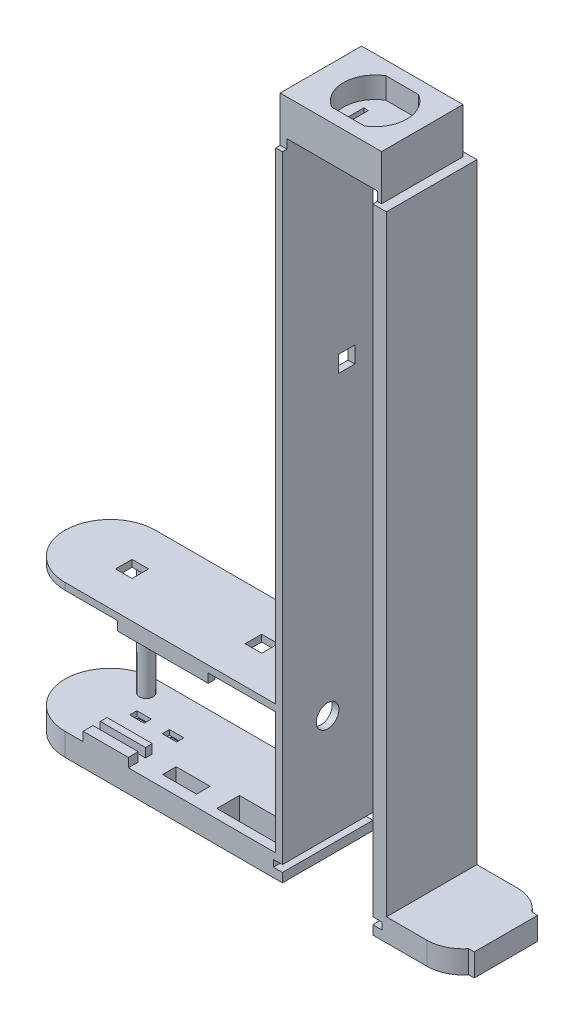
SolidWorks part; units mm, degrees
material "PVC Rigid"
ref_plane "Front Plane" through (0, 0, 0) normal (0, 0, 1) x (1, 0, 0)
ref_plane "Top Plane" through (0, 0, 0) normal (0, 1, 0) x (1, 0, 0)
ref_plane "Right Plane" through (0, 0, 0) normal (1, 0, 0) x (0, 0, -1)
sketch "Sketch2" plane through (0, 0, 0) normal (0, 1, 0) x (1, 0, 0)
  line L0 (-97.0727, 0) -> (97.0727, 0) construction
  line L1 (0, 44.8562) -> (0, -44.8562) construction
  line L2 (0, 10) -> (80, 10)
  line L3 (0, -10) -> (80, -10)
  line L5 (86.245, 7) -> (87.485, 7)
  line L6 (87.485, 7) -> (87.485, -7)
  line L7 (87.485, -7) -> (86.245, -7)
  arc A0 (0, 10) -> (0, -10) centre (0, 0) ccw
  arc A1 (80, 10) -> (86.245, 7) centre (80, 2) cw
  arc A2 (80, -10) -> (86.245, -7) centre (80, -2) ccw
  dimension "D1" = 10
  dimension "D4" = 8
  dimension "D5" = 8
  dimension "D2" = 80
  dimension "D3" = 80
  dimension "D6" = 7
  dimension "D7" = 7
  dimension "D8" = 1.24
  dimension "D9" = 1.24
extrude "Boss-Extrude1" add sketch "Sketch2" along normal blind 5
sketch "Sketch3" plane through (0, 5, 0) normal (0, 1, 0) x (1, 0, 0)
  line L0 (48.0657, 27.5037) -> (48.0657, -29.4655) construction
  line L2 (80, 10) -> (0, 10) construction
  line L3 (48.0657, 10) -> (46.5657, 10)
  line L4 (48.0657, 10) -> (48.0657, -10)
  line L5 (48.0657, -10) -> (46.5657, -10)
  line L6 (46.5657, 10) -> (46.5657, -10)
  line L7 (0, -10) -> (80, -10) construction
  line L8 (80, 10) -> (0, 10) construction
  line L9 (68.0657, 10) -> (71.0657, 10)
  line L10 (68.0657, 10) -> (68.0657, -10)
  line L11 (68.0657, -10) -> (71.0657, -10)
  line L12 (71.0657, 10) -> (71.0657, -10)
  line L13 (0, -10) -> (80, -10) construction
  dimension "D1" = 1.5
  dimension "D2" = 3
  dimension "D3" = 20
extrude "Boss-Extrude2" add sketch "Sketch3" along normal blind 145
ref_plane "Plane1" through (0, 32, 0) normal (0, 1, 0) x (1, 0, 0)
sketch "Sketch4" plane through (0, 32, 0) normal (0, 1, 0) x (1, 0, 0)
  line L0 (0, 10) -> (46.5657, 10)
  line L1 (46.5657, 10) -> (46.5657, -10) construction
  line L2 (46.5657, 10) -> (46.5657, -10) construction
  line L3 (0, -10) -> (46.5657, -10)
  line L4 (46.5657, -10) -> (46.5657, 10)
  arc A0 (0, 10) -> (0, -10) centre (0, 0) ccw
  arc A1 (0, 10) -> (0, -10) centre (0, 0) ccw construction
extrude "Boss-Extrude3" add sketch "Sketch4" along normal blind 1.5
sketch "Sketch5" plane through (0, 150, 0) normal (0, 1, 0) x (1, 0, 0)
  line L1 (68.0657, 10) -> (48.0657, 10)
  line L2 (68.0657, 10) -> (68.0657, -10)
  line L3 (68.0657, -10) -> (48.0657, -10)
  line L4 (48.0657, 10) -> (48.0657, -10)
extrude "Boss-Extrude4" add sketch "Sketch5" against normal blind 8
sketch "Sketch7" plane through (0, 0, 10) normal (0, 0, 1) x (1, 0, 0)
  line L0 (48.0657, 16.8561) -> (48.0657, -1.4698) construction
  line L1 (48.0657, 142) -> (48.0657, 5) construction
  line L2 (68.0657, 16.8561) -> (68.0657, -2.6062) construction
  line L3 (68.0657, 142) -> (68.0657, 5) construction
  line L4 (48.0657, 5) -> (48.0657, 3.5)
  line L5 (48.0657, 3.5) -> (46.0657, 3.5)
  line L6 (46.0657, 3.5) -> (46.0657, 2)
  line L7 (46.0657, 2) -> (48.0657, 2)
  line L8 (48.0657, 2) -> (48.0657, 0)
  line L9 (48.0657, 0) -> (68.0657, 0)
  line L10 (0, 0) -> (80, 0) construction
  line L11 (68.0657, 0) -> (68.0657, 2)
  line L12 (68.0657, 2) -> (70.0657, 2)
  line L13 (70.0657, 2) -> (70.0657, 3.5)
  line L14 (70.0657, 3.5) -> (68.0657, 3.5)
  line L15 (68.0657, 3.5) -> (68.0657, 5)
  line L16 (68.0657, 5) -> (48.0657, 5)
  line L17 (0, 5) -> (46.5657, 5) construction
  line L18 (0, 5) -> (0, 0) construction
  dimension "D1" = 1.5
  dimension "D2" = 1.5
  dimension "D3" = 1.5
  dimension "D4" = 1.5
  dimension "D5" = 2
  dimension "D6" = 2
  dimension "D7" = 48.0657
extrude "Cut-Extrude1" cut sketch "Sketch7" against normal blind 20
sketch "Sketch8" plane through (0, 5, 0) normal (0, 1, 0) x (1, 0, 0)
  circle A0 centre (1.6533, 6.3042) radius 1.5
  dimension "D1" = 1.5
extrude "Boss-Extrude5" add sketch "Sketch8" along normal up to next
sketch "Sketch9" plane through (46.5657, 0, 0) normal (-1, 0, 0) x (0, 0, 1)
  line L0 (10, 32) -> (-10, 32) construction
  line L1 (10, 32) -> (10, 5) construction
  circle A0 centre (0, 27) radius 2.5
  dimension "D1" = 5
  dimension "D2" = 5
  dimension "D3" = 10
extrude "Cut-Extrude2" cut sketch "Sketch9" against normal blind 1.5 contours A0
sketch "Sketch10" plane through (0, 0, 0) normal (0, 1, 0) x (1, 0, 0)
  line L0 (71.0657, 21.0712) -> (71.0657, -27.514) construction
  line L1 (71.0657, -10) -> (71.0657, 10) construction
  line L2 (71.0657, 10) -> (91.8634, 10) construction
  line L3 (71.0657, -10) -> (94.8231, -10) construction
  line L4 (80, -10) -> (80, 10) construction
  dimension "D1" = 8.9343
  dimension "D2" = 20
sketch "Sketch11" plane through (0, 33.5, 0) normal (0, 1, 0) x (1, 0, 0)
  line L0 (0, 0) -> (40.7107, 0) construction
  line L1 (3, 1.825) -> (6.65, 1.825)
  line L2 (3, 1.825) -> (3, -1.825)
  line L3 (3, -1.825) -> (6.65, -1.825)
  line L4 (6.65, 1.825) -> (6.65, -1.825)
  line L6 (31.65, 1.825) -> (35.3, 1.825)
  line L7 (31.65, 1.825) -> (31.65, -1.825)
  line L8 (31.65, -1.825) -> (35.3, -1.825)
  line L9 (35.3, 1.825) -> (35.3, -1.825)
  point P11 (35.3, 0)
  dimension "D1" = 3.65
  dimension "D2" = 3.65
  dimension "D3" = 3
  dimension "D4" = 1.825
  dimension "D5" = 3.65
  dimension "D6" = 3.65
  dimension "D7" = 3.65
  dimension "D8" = 25
extrude "Cut-Extrude3" cut sketch "Sketch11" against normal up to next
sketch "Sketch12" plane through (46.5657, 0, 0) normal (-1, 0, 0) x (0, 0, 1)
  line L0 (-10, 150) -> (-10, 33.5) construction
  line L1 (-6, 95) -> (-2.35, 95)
  line L2 (-6, 95) -> (-6, 91.35)
  line L3 (-6, 91.35) -> (-2.35, 91.35)
  line L4 (-2.35, 95) -> (-2.35, 91.35)
  line L5 (-10, 150) -> (10, 150) construction
  dimension "D1" = 3.65
  dimension "D2" = 4
  dimension "D3" = 55
extrude "Cut-Extrude4" cut sketch "Sketch12" against normal up to next
sketch "Sketch13" plane through (0, 0, 0) normal (0, 0, 1) x (1, 0, 0)
  line L0 (48.0657, 0) -> (48.0657, 150) construction
  line L1 (46.5657, 150) -> (71.0657, 150) construction
  dimension "D1" = 150
sketch "Sketch14" plane through (0, 150, 0) normal (0, 1, 0) x (1, 0, 0)
  line L0 (54.9613, 6) -> (62.1713, 6)
  line L1 (54.9613, -6) -> (62.1713, -6)
  line L3 (46.5657, -10) -> (71.0657, -10) construction
  line L4 (46.5657, 10) -> (46.5657, -10) construction
  arc A0 (54.9613, 6) -> (54.9613, -6) centre (58.5657, 0) ccw
  arc A1 (62.1713, 6) -> (62.1713, -6) centre (58.5669, 0) cw
  dimension "D2" = 14
  dimension "D1" = 12
  dimension "D3" = 7.21
  dimension "D4" = 10
  dimension "D5" = 12
extrude "Cut-Extrude5" cut sketch "Sketch14" against normal blind 4.7
sketch "Sketch15" plane through (0, 145.3, 0) normal (0, 1, 0) x (1, 0, 0)
  line L0 (53.9613, 2.1) -> (53.9613, -2.1)
  line L1 (53.9613, 2.1) -> (54.9613, 2.1)
  line L2 (54.9613, 2.1) -> (54.9613, -2.1)
  line L3 (54.9613, -2.1) -> (53.9613, -2.1)
  line L5 (62.1713, 6) -> (54.9613, 6) construction
  line L6 (58.5663, 7.0131) -> (58.5663, -6.3145) construction
  line L8 (62.1713, 2.1) -> (62.1713, -2.1)
  line L9 (63.1713, 2.1) -> (62.1713, 2.1)
  line L10 (63.1713, 2.1) -> (63.1713, -2.1)
  line L11 (62.1713, -2.1) -> (63.1713, -2.1)
  dimension "D1" = 4.2
  dimension "D2" = 1
  dimension "D3" = 3.9
  dimension "D4" = 0
  dimension "D5" = 3.605
extrude "Cut-Extrude7" cut sketch "Sketch15" against normal up to next
sketch "Sketch17" plane through (0, 32, 0) normal (0, -1, 0) x (1, 0, 0)
  line L1 (11.65, 10) -> (31.65, 10)
  line L2 (11.65, 10) -> (11.65, 8.5)
  line L3 (11.65, 8.5) -> (31.65, 8.5)
  line L4 (31.65, 10) -> (31.65, 8.5)
  line L5 (11.65, 10) -> (31.65, 8.5) construction
  line L6 (11.65, 8.5) -> (31.65, 10) construction
  line L7 (0, 10) -> (46.5657, 10) construction
  line L8 (31.65, 1.825) -> (31.65, -1.825) construction
  line L10 (11.65, 6.9) -> (31.65, 6.9)
  line L11 (11.65, 6.9) -> (11.65, 5.4)
  line L12 (11.65, 5.4) -> (31.65, 5.4)
  line L13 (31.65, 6.9) -> (31.65, 5.4)
  point P0 (21.65, 9.25)
  dimension "D1" = 1.5
  dimension "D2" = 20
  dimension "D3" = 1.5
  dimension "D4" = 20
  dimension "D5" = 1.6
extrude "Boss-Extrude6" add sketch "Sketch17" along normal blind 2
sketch "Sketch19" plane through (0, 0, 0) normal (0, -1, 0) x (1, 0, 0)
  line L0 (48.0657, -10) -> (48.0657, 10) construction
  line L1 (31.5657, 8) -> (44.5657, 8)
  line L2 (31.5657, 8) -> (31.5657, 3)
  line L3 (31.5657, 3) -> (44.5657, 3)
  line L4 (44.5657, 8) -> (44.5657, 3)
  line L5 (19.0657, 7.5) -> (26.5657, 7.5)
  line L6 (19.0657, 7.5) -> (19.0657, 4.5)
  line L7 (19.0657, 4.5) -> (26.5657, 4.5)
  line L8 (26.5657, 7.5) -> (26.5657, 4.5)
  line L9 (0, 10) -> (48.0657, 10) construction
  dimension "D1" = 3.5
  dimension "D2" = 5
  dimension "D3" = 13
  dimension "D4" = 5
  dimension "D5" = 2
  dimension "D6" = 1.5
  dimension "D7" = 7.5
  dimension "D8" = 3
extrude "Cut-Extrude8" cut sketch "Sketch19" against normal up to next
sketch "Sketch20" plane through (0, 5, 0) normal (0, 1, 0) x (1, 0, 0)
  line L0 (0, -10) -> (46.5657, -10) construction
  line L1 (4, -10) -> (14, -10)
  line L2 (4, -10) -> (4, -7.8168)
  line L3 (4, -7.8168) -> (14, -7.8168)
  line L4 (14, -10) -> (14, -7.8168)
  line L6 (4, -4.7168) -> (14, -4.7168)
  line L7 (4, -4.7168) -> (4, -6.2168)
  line L8 (4, -6.2168) -> (14, -6.2168)
  line L9 (14, -4.7168) -> (14, -6.2168)
  point P10 (14, -8.9084)
  point P12 (9, -4.7168)
  dimension "D1" = 10
  dimension "D2" = 10
  dimension "D3" = 1.6
  dimension "D4" = 4
  dimension "D5" = 4
  dimension "D6" = 1.5
extrude "Boss-Extrude7" add sketch "Sketch20" along normal blind 2
sketch "Sketch21" plane through (0, 150, 0) normal (0, 1, 0) x (1, 0, 0)
  line L0 (46.5657, 10) -> (71.0657, 10)
  line L1 (71.0657, 10) -> (71.0657, -10)
  line L2 (71.0657, -10) -> (46.5657, -10)
  line L3 (46.5657, -10) -> (46.5657, -9)
  line L4 (46.5657, -10) -> (46.5657, 10) construction
  line L5 (46.5657, -9) -> (68.9957, -9)
  line L6 (68.9957, -9) -> (68.9957, 9)
  line L7 (68.9957, 9) -> (46.5657, 9)
  line L8 (46.5657, 9) -> (46.5657, 10)
  dimension "D1" = 1
  dimension "D2" = 2.07
  dimension "D3" = 1
extrude "Cut-Extrude9" cut sketch "Sketch21" against normal blind 10
sketch "Sketch22" plane through (0, 5, 0) normal (0, 1, 0) x (1, 0, 0)
  line L0 (14, -4.7168) -> (4, -4.7168) construction
  line L1 (4, 1.8832) -> (7.2, 1.8832)
  line L2 (4, 1.8832) -> (4, 0.2832)
  line L3 (4, 0.2832) -> (7.2, 0.2832)
  line L4 (7.2, 1.8832) -> (7.2, 0.2832)
  line L5 (11.2, 1.8832) -> (14.4, 1.8832)
  line L6 (11.2, 1.8832) -> (11.2, 0.2832)
  line L7 (11.2, 0.2832) -> (14.4, 0.2832)
  line L8 (14.4, 1.8832) -> (14.4, 0.2832)
  line L9 (4, -4.7168) -> (4, -6.2168) construction
  point P8 (11.2, 1.0832)
  dimension "D1" = 3.2
  dimension "D2" = 3.2
  dimension "D3" = 1.6
  dimension "D4" = 1.6
  dimension "D5" = 4
  dimension "D6" = 5
extrude "Cut-Extrude10" cut sketch "Sketch22" against normal blind 1.1
sketch "Sketch23" plane through (0, 3.9, 0) normal (0, 1, 0) x (1, 0, 0)
  line L0 (12.05, 1.0832) -> (13.55, 1.0832) construction
  line L1 (12.05, 1.6832) -> (13.55, 1.6832)
  line L2 (12.05, 0.4832) -> (13.55, 0.4832)
  line L5 (14.4, 1.8832) -> (11.2, 1.8832) construction
  line L6 (14.4, 0.2832) -> (14.4, 1.8832) construction
  arc A0 (12.05, 1.6832) -> (12.05, 0.4832) centre (12.05, 1.0832) ccw
  arc A1 (13.55, 0.4832) -> (13.55, 1.6832) centre (13.55, 1.0832) ccw
  point P2 (12.8, 1.0832)
  dimension "D3" = 0.6
  dimension "D1" = 1.5
  dimension "D2" = 0.8
  dimension "D4" = 1.6
extrude "Cut-Extrude11" cut sketch "Sketch23" against normal up to next
sketch "Sketch25" plane through (0, 3.9, 0) normal (0, 1, 0) x (1, 0, 0)
  line L0 (4.8, 1.0832) -> (6.4, 1.0832) construction
  line L1 (4.8, 1.6832) -> (6.4, 1.6832)
  line L2 (4.8, 0.4832) -> (6.4, 0.4832)
  line L3 (7.2, 1.8832) -> (4, 1.8832) construction
  line L4 (7.2, 0.2832) -> (7.2, 1.8832) construction
  arc A0 (4.8, 1.6832) -> (4.8, 0.4832) centre (4.8, 1.0832) ccw
  arc A1 (6.4, 0.4832) -> (6.4, 1.6832) centre (6.4, 1.0832) ccw
  point P2 (5.6, 1.0832)
  dimension "D2" = 0.6
  dimension "D1" = 0.8
  dimension "D3" = 1.6
  dimension "D4" = 1.6
extrude "Cut-Extrude12" cut sketch "Sketch25" against normal up to next
sketch "Sketch26" plane through (0, 0, 0) normal (0, -1, 0) x (1, 0, 0)
  line L0 (4.2, -4.6832) -> (18.426, -4.6832) construction
  line L1 (11.45, -1.0832) -> (11.45, -6.8949) construction
  line L2 (4.2, -1.0832) -> (4.2, -6.8949) construction
  line L3 (4.8, -1.6832) -> (6.4, -1.6832) construction
  arc A0 (12.05, -0.4832) -> (12.05, -1.6832) centre (12.05, -1.0832) ccw construction
  arc A1 (4.8, -0.4832) -> (4.8, -1.6832) centre (4.8, -1.0832) ccw construction
  text T0 "Charge Full" font "Century Gothic" height in points 3
  text T1 "                        Charging" font "Century Gothic" height in points 3
  dimension "D1" = 3
extrude "Boss-Extrude8" add sketch "Sketch26" along normal blind 0.1
